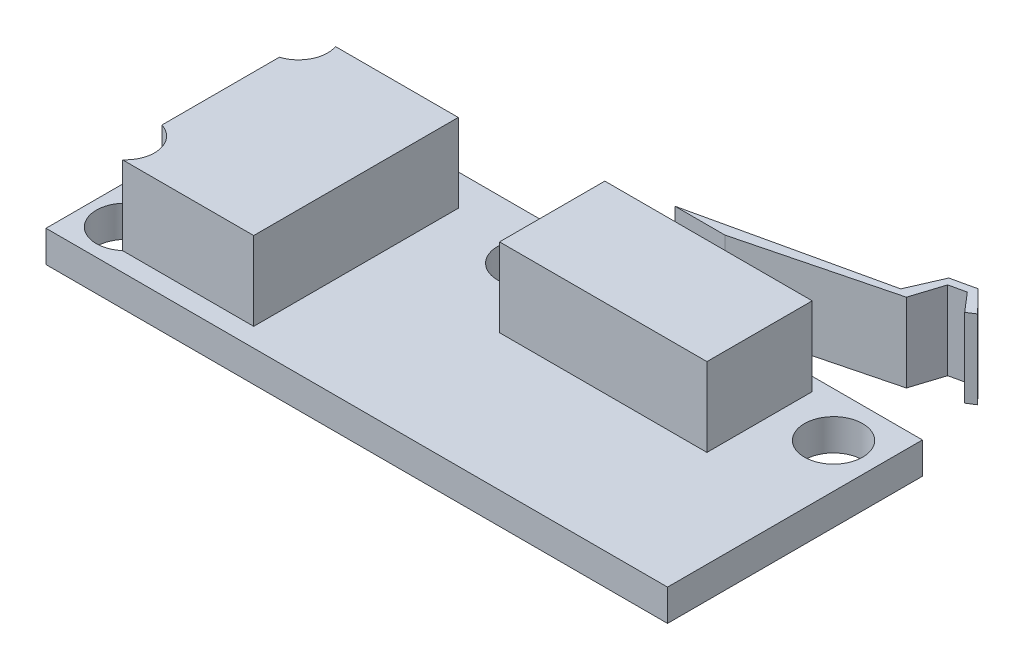
SolidWorks part; units mm, degrees
ref_plane "Front Plane" through (0, 0, 0) normal (0, 0, 1) x (1, 0, 0)
ref_plane "Top Plane" through (0, 0, 0) normal (0, 1, 0) x (1, 0, 0)
ref_plane "Right Plane" through (0, 0, 0) normal (1, 0, 0) x (0, 0, -1)
sketch "Sketch1" plane through (0, 0, 0) normal (0, 1, 0) x (1, 0, 0)
  line L0 (105.7055, 207.0232) -> (543.2107, 207.0232) construction
  line L1 (17.2, 13.35) -> (36.7, 13.35) construction
  line L2 (0, 0) -> (39.5, 0)
  line L3 (0, 0) -> (0, 16.2)
  line L4 (0, 16.2) -> (39.5, 16.2)
  line L5 (39.5, 0) -> (39.5, 16.2)
  line L6 (36.7, 13.35) -> (39.5, 13.35) construction
  line L7 (2.45, 13.6) -> (2.45, 2.6) construction
  line L8 (2.45, 13.6) -> (2.45, 16.2) construction
  line L9 (2.45, 2.6) -> (2.45, 0) construction
  circle A0 centre (2.45, 2.6) radius 1.85
  circle A1 centre (2.45, 13.6) radius 1.85
  circle A2 centre (17.2, 13.35) radius 1.85
  circle A3 centre (36.7, 13.35) radius 1.85
  point P15 (2.4499, 2.651)
  dimension "D7" = 3.7
  dimension "D1" = 39.5
  dimension "D2" = 16.2
  dimension "D3" = 19.5
  dimension "D4" = 2.8
  dimension "D5" = 2.85
  dimension "D6" = 11
  dimension "D8" = 2.45
extrude "Boss-Extrude1" add sketch "Sketch1" along normal blind 2
sketch "Sketch3" plane through (0, 2, 0) normal (0, 1, 0) x (1, 0, 0)
  line L0 (162.1986, 317.3062) -> (825.532, 317.3062) construction
  line L1 (19.9931, 15.3536) -> (35.4977, 18.8253)
  line L2 (3, 14.2) -> (12, 14.2)
  line L3 (3, 14.2) -> (3, 1.2)
  line L4 (3, 1.2) -> (12, 1.2)
  line L5 (12, 14.2) -> (12, 1.2)
  line L6 (20.1617, 15.3536) -> (33.3405, 15.3536)
  line L7 (20.1617, 15.3536) -> (20.1617, 8.663)
  line L8 (20.1617, 8.663) -> (33.3405, 8.663)
  line L9 (33.3405, 15.3536) -> (33.3405, 8.663)
  line L10 (35.4977, 18.8253) -> (36.4246, 20.9487)
  line L11 (36.4246, 20.9487) -> (37.9425, 21.2886)
  line L12 (37.9425, 21.2886) -> (39.3233, 19.887)
  line L13 (39.3233, 19.887) -> (38.8177, 19.5668)
  line L14 (38.8177, 19.5668) -> (37.7897, 20.7633)
  line L15 (37.7897, 20.7633) -> (36.7657, 20.534)
  line L16 (36.7657, 20.534) -> (36.1345, 18.5473)
  line L17 (36.1345, 18.5473) -> (23.6333, 15.3536)
  line L18 (39.5, 16.2) -> (0, 16.2) construction
  line L19 (0, 16.2) -> (0, 0) construction
  line L20 (39.5, 0) -> (39.5, 16.2) construction
  line M5 (39.5, 16.2) -> (0, 16.2)
  circle M6 centre (2.45, 2.6) radius 1.85
  circle M7 centre (2.45, 13.6) radius 1.85
  dimension "D1" = 13
  dimension "D2" = 9
  dimension "D3" = 2
  dimension "D4" = 3
  dimension "D5" = 0.8464
  dimension "D6" = 6.1595
  dimension "D7" = 13.1789
  dimension "D8" = 6.6906
extrude "Boss-Extrude2" add sketch "Sketch3" along normal blind 5 contours L5 L2 L3 L4 M7 M6 | L9 L6 L7 L8 | L17 L16 L15 L14 L13 L12 L11 L10 L1 M5
